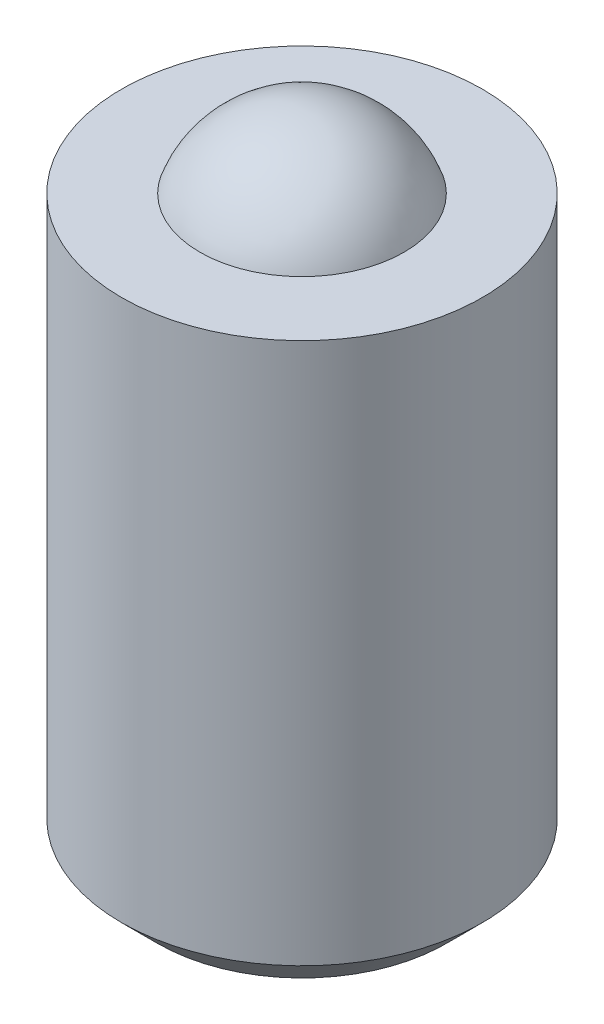
SolidWorks part; units mm, degrees
ref_plane "前视基准面" through (0, 0, 0) normal (0, 0, 1) x (1, 0, 0)
ref_plane "上视基准面" through (0, 0, 0) normal (0, 1, 0) x (1, 0, 0)
ref_plane "右视基准面" through (0, 0, 0) normal (1, 0, 0) x (0, 0, -1)
sketch "草图1" plane through (0, 0, 0) normal (1, 0, 0) x (0, 0, -1)
  line L0 (0, 46.2984) -> (0, -39.6162) construction
  line L1 (-16.4783, 0) -> (19.9104, 0) construction
  line L2 (-2.8284, 0) -> (-5, 0)
  line L3 (-5, 0) -> (-5, -15)
  line L4 (-5, -15) -> (-4, -16)
  line L5 (-4, -16) -> (0, -16)
  line L6 (0, 2) -> (0, -16)
  arc A0 (0, 2) -> (-2.8284, 0) centre (0, -1) ccw
  dimension "D1" = 3
  dimension "D4" = 16
  dimension "D2" = 5
  dimension "D3" = 1
  dimension "D5" = 1
  dimension "D6" = 1
revolve "旋转1" add sketch "草图1" angle 360 about L0
